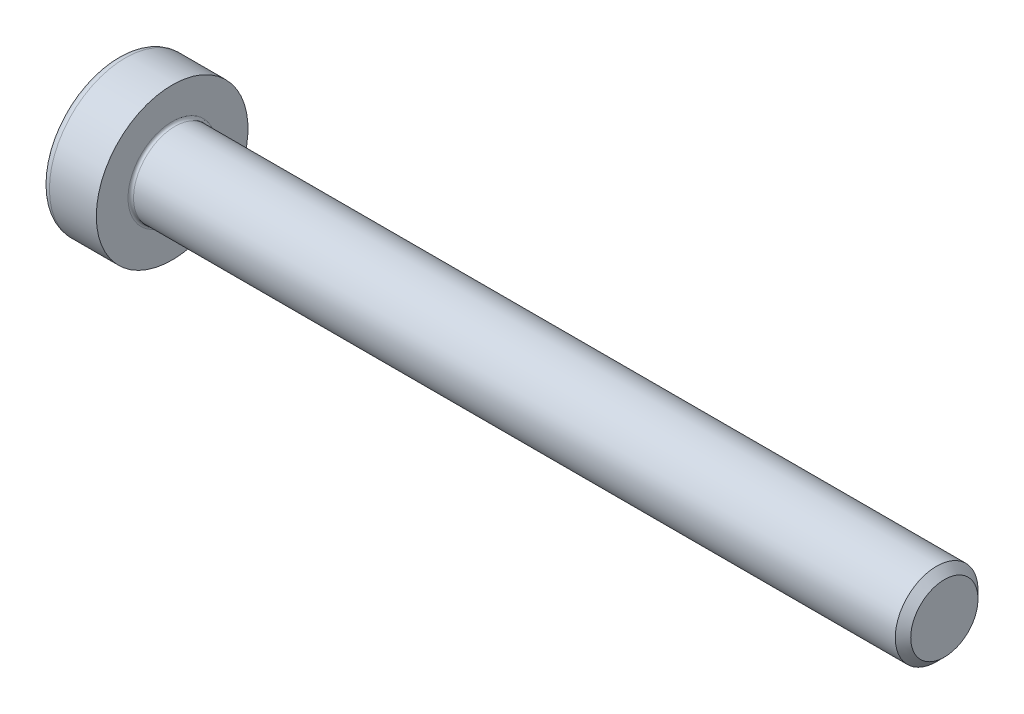
SolidWorks part; units mm, degrees
revolve "Base-Revolve" add sketch "BodySke"
sketch "BodySke" plane through (0, 0, 0) normal (0, 0, 1) x (1, 0, 0)
  line L0 (0, 0) -> (0, 2.75)
  line L1 (0, 2.75) -> (2, 2.75)
  line L2 (2, 2.75) -> (2, 1.5)
  line L3 (2, 1.5) -> (29.7195, 1.5)
  line L4 (30, 1.2195) -> (30, 0)
  line L5 (30, 0) -> (0, 0)
  line L6 (-31.75, 0) -> (127, 0) construction
  line L8 (30, 1.2195) -> (29.7195, 1.5)
  line L10 (30, -1.2195) -> (29.7195, -1.5) construction
  line L11 (2.5, 4.525) -> (2.5, -1.825) construction
  line L12 (2, 4.525) -> (2, -1.825) construction
  line L13 (-30, 4.525) -> (-30, -1.825) construction
  dimension "Head_ht" = 2
  dimension "Length" = 28
  dimension "Body_ch_ang" = 45
  dimension "Diameter" = 3
  dimension "Minor_dia" = 2.439
  dimension "Advance" = 0.5
  dimension "Thread_nom" = 28
  dimension "Thread_length" = 60
  dimension "Head_dia" = 5.5
cosmetic thread "ThreadCosmetic" [suppressed]
fillet "Fillet1" radius 0.1 1 edges at (2, 0, 1.5)
fillet "Fillet2" radius 0.3 1 edges at (0, 0, 2.75)
ref_plane "Plane1" through (0, 0, 0) normal (0, 0, 1) x (1, 0, 0)
ref_plane "Plane2" through (0, 0, 0) normal (0, 1, 0) x (1, 0, 0)
ref_plane "Plane3" through (0, 0, 0) normal (1, 0, 0) x (0, 0, -1)
sketch "Sketch2" plane through (0, 0, 0) normal (0, 0, 1) x (1, 0, 0)
  line L0 (0, 1) -> (1.5, 1)
  line L1 (1.5, 1) -> (2.0774, 0)
  line L2 (-31.75, 0) -> (127, 0) construction
  line L3 (2.0774, 0) -> (0, 0)
  line L4 (0, 0) -> (0, 1)
  line L6 (0, 0) -> (47.625, 0) construction
  dimension "D1" = 1
  dimension "D2" = 60
  dimension "Depth" = 1.5
revolve "Hex-PreBroach" cut sketch "Sketch2" angle 360 about L6
sketch "Sketch3" plane through (0, 0, 0) normal (-1, 0, 0) x (0, 0.5, 0.866)
  line L0 (0.5774, 1) -> (-0.5774, 1)
  line L1 (-0.5774, 1) -> (-1.1547, 0)
  line L2 (0.5774, 1) -> (1.1547, 0)
  line L3 (0.5774, -1) -> (1.1547, 0)
  line L4 (0.5774, -1) -> (-0.5774, -1)
  line L5 (-0.5774, -1) -> (-1.1547, 0)
  dimension "D1" = 1
  dimension "D2" = 1
  dimension "Hex_size" = 2
extrude "Hex" cut sketch "Sketch3" against normal blind 1.5
sketch "ThdSchSke" plane through (0, 0, 0) normal (0, 0, 1) x (1, 0, 0)
  line L0 (3.5, -1.2195) -> (3.3036, -1.5)
  line L1 (3.5, -1.2195) -> (3.6964, -1.5)
  line L2 (3.6964, -1.5) -> (3.6964, -1.875)
  line L3 (-3.175, 0) -> (5.1513, 0) construction
  line L4 (0, 2.45) -> (0, -2.45) construction
  line L5 (3.6964, -1.875) -> (3.3036, -1.875)
  line L6 (3.3036, -1.875) -> (3.3036, -1.5)
  dimension "Thread_minor" = 2.439
  dimension "Diameter" = 3
  dimension "Start" = 3.5
revolve "ThreadSchematic" [suppressed] cut sketch "ThdSchSke" angle 360 about L3
pattern_linear "ThdSchPat" [suppressed]
equation "\"D2@Sketch3\" = \"Hex_size@Sketch3\" / 2"
equation "\"D1@Sketch3\" = \"Hex_size@Sketch3\" / 2"
equation "\"D1@Sketch2\" = \"Hex_size@Sketch3\" / 2"
equation "\"Thread_minor@ThreadCosmetic\"  =  \"Minor_dia@BodySke\""
equation "\"Depth@Sketch2\" =  \"Key_eng@Hex\""
equation "\"Thread_length@ThreadCosmetic\" = ((sgn( (\"Length@BodySke\" - \"Advance@BodySke\" * 3.0) - \"Thread_nom@BodySke\" )-1)*( (\"Length@BodySke\" - \"Advance@BodySke\" * 3.0) - \"Thread_nom@BodySke\" ))/-2+ \"Thread_nom@BodySke\""
equation "\"Thread_minor@ThdSchSke\" = \"Minor_dia@BodySke\""
equation "\"Diameter@ThdSchSke\" = \"Diameter@BodySke\""
equation "\"Overcut@ThdSchSke\" = \"Diameter@BodySke\" * 1.25"
equation "\"Start@ThdSchSke\" = \"Head_ht@BodySke\" + \"Length@BodySke\" - \"Thread_length@ThreadCosmetic\"  '---Non-countersunk---"
equation "\"Num_threads@ThdSchPat\" = int( \"Thread_length@ThreadCosmetic\" / \"Advance@BodySke\" + 0.999 )  + 1"
equation "\"Advance@ThdSchPat\" = \"Thread_length@ThreadCosmetic\" /  (\"Num_threads@ThdSchPat\" - 1) 'relax it"
equation "\"Num_threads@ThdSchPat\" = \"Num_threads@ThdSchPat\" - sgn( \"Num_threads@ThdSchPat\" - 1) '---chamfered tips only---"
